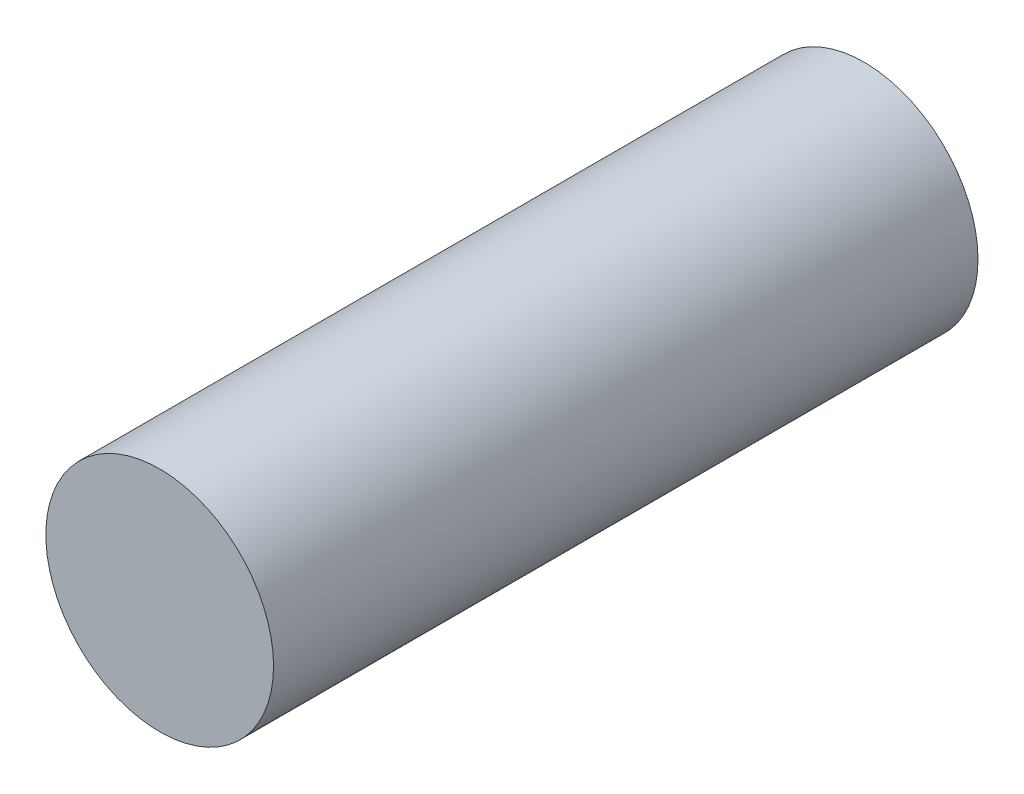
SolidWorks part; units mm, degrees
ref_plane "前视基准面" through (0, 0, 0) normal (0, 0, 1) x (1, 0, 0)
ref_plane "上视基准面" through (0, 0, 0) normal (0, 1, 0) x (1, 0, 0)
ref_plane "右视基准面" through (0, 0, 0) normal (1, 0, 0) x (0, 0, -1)
sketch "草图1" plane through (0, 0, 0) normal (0, 0, 1) x (1, 0, 0)
  circle A2 centre (-1, 0) radius 0.3232
extrude "凸台-拉伸1" add sketch "草图1" along normal mid plane 2
